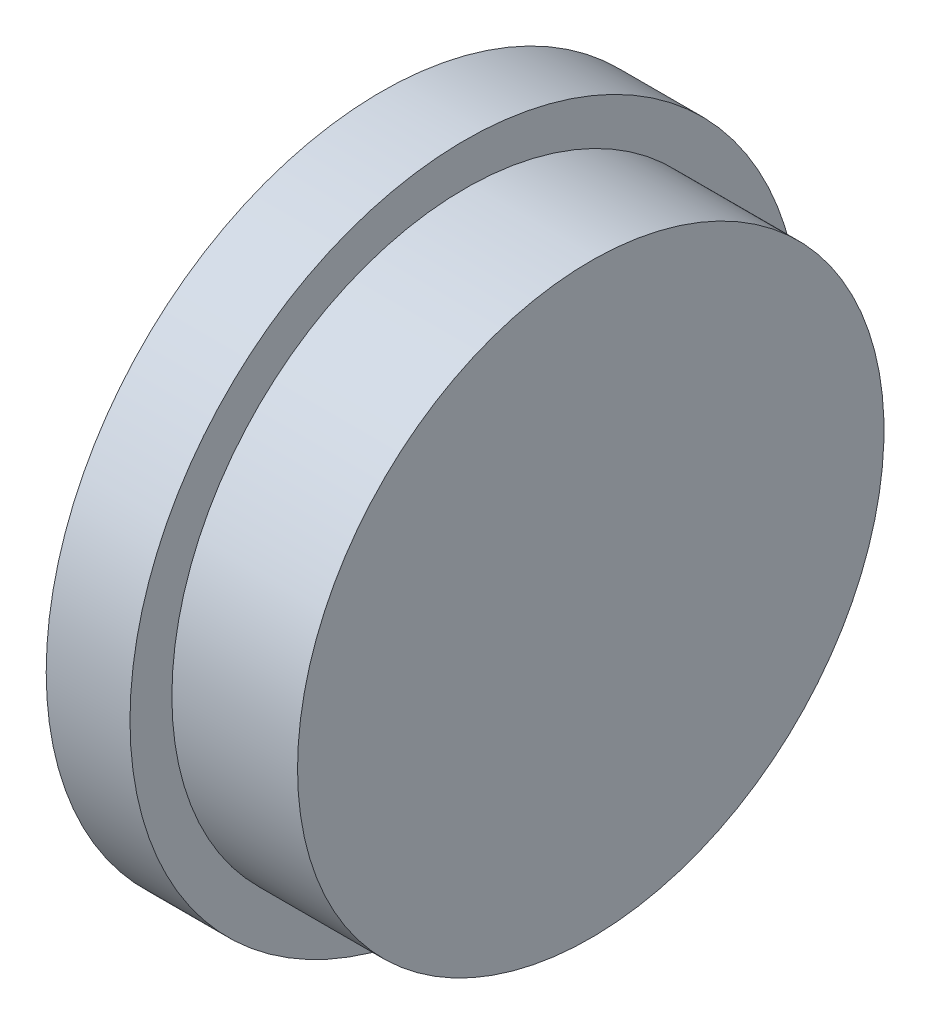
SolidWorks part; units mm, degrees
ref_plane "Plan de face" through (0, 0, 0) normal (0, 0, 1) x (1, 0, 0)
ref_plane "Plan de dessus" through (0, 0, 0) normal (0, 1, 0) x (1, 0, 0)
ref_plane "Plan de droite" through (0, 0, 0) normal (1, 0, 0) x (0, 0, -1)
sketch "Esquisse6" plane through (0, 0, 0) normal (0, 0, 1) x (1, 0, 0)
  line L0 (0, 0) -> (15, 0) construction
  line L1 (15, 0) -> (13, 0)
  line L2 (13, 0) -> (13, 16)
  line L3 (15, 0) -> (15, 21)
  line L4 (13, 16) -> (0, 16)
  line L5 (0, 16) -> (0, 24)
  line L6 (0, 24) -> (6, 24)
  line L7 (6, 24) -> (6, 21)
  line L8 (6, 21) -> (15, 21)
  dimension "D1" = 15
  dimension "D2" = 2
  dimension "D3" = 16
  dimension "D4" = 21
  dimension "D5" = 13
  dimension "D6" = 8
  dimension "D7" = 6
  dimension "D8" = 3
revolve "Révolution1" add sketch "Esquisse6" angle 360 about L0
